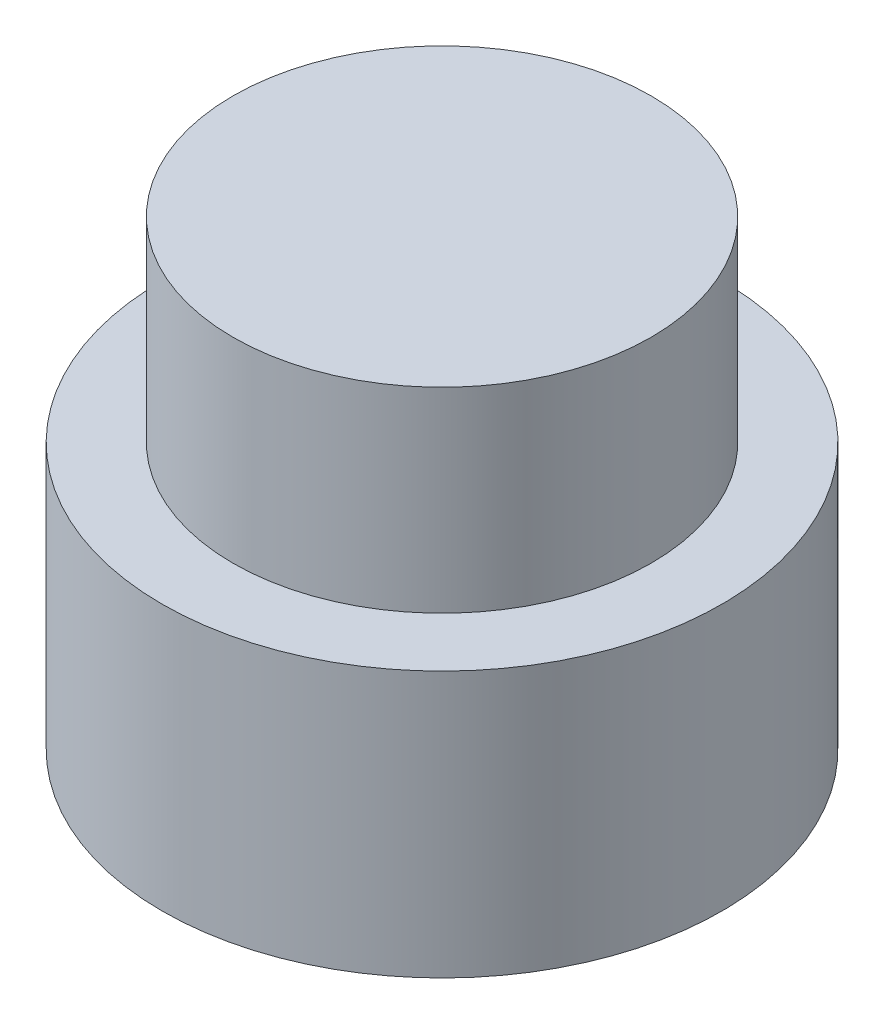
SolidWorks part; units mm, degrees
ref_plane "Front Plane" through (0, 0, 0) normal (0, 0, 1) x (1, 0, 0)
ref_plane "Top Plane" through (0, 0, 0) normal (0, 1, 0) x (1, 0, 0)
ref_plane "Right Plane" through (0, 0, 0) normal (1, 0, 0) x (0, 0, -1)
sketch "Sketch1" plane through (0, 0, 0) normal (0, 0, 1) x (1, 0, 0)
  line L0 (0, 13.0224) -> (0, -6.3849) construction
  line L1 (0, 0) -> (7.9, 0)
  line L2 (7.9, 0) -> (7.9, 7.5)
  line L3 (7.9, 7.5) -> (5.9, 7.5)
  line L4 (5.9, 7.5) -> (5.9, 13.0224)
  line L5 (5.9, 13.0224) -> (0, 13.0224)
  line L6 (0, 13.0224) -> (0, 0)
  dimension "D1" = 7.9
  dimension "D2" = 7.5
  dimension "D3" = 2
revolve "Revolve1" add sketch "Sketch1" angle 360 about L6
sketch "Sketch2" plane through (0, 0, 0) normal (0, -1, 0) x (1, 0, 0)
  circle A0 centre (0, 0) radius 2.5
  dimension "D1" = 5
extrude "Cut-Extrude1" cut sketch "Sketch2" against normal blind 10
